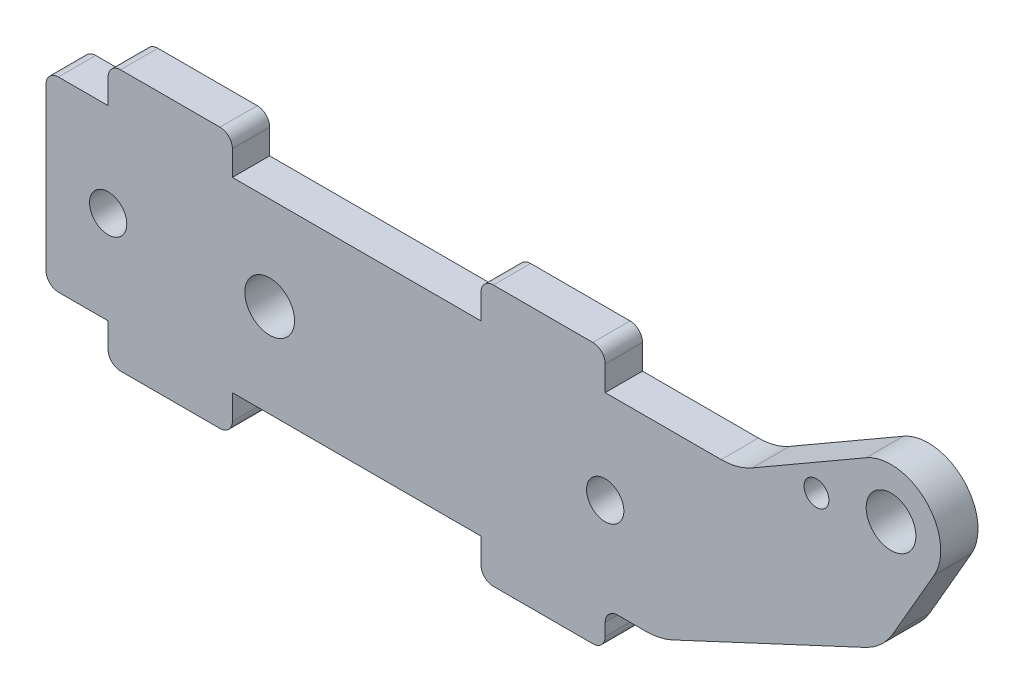
SolidWorks part; units mm, degrees
material "Thornel Mat VMA"
ref_plane "前视基准面" through (0, 0, 0) normal (0, 0, 1) x (1, 0, 0)
ref_plane "上视基准面" through (0, 0, 0) normal (0, 1, 0) x (1, 0, 0)
ref_plane "右视基准面" through (0, 0, 0) normal (1, 0, 0) x (0, 0, -1)
sketch "草图1" plane through (0, 0, 0) normal (0, 0, 1) x (1, 0, 0)
  line L0 (0, 0) -> (45, 0) construction
  line L1 (0, 7.5) -> (5, 7.5)
  line L2 (5, 7.5) -> (5, 10.5)
  line L3 (5, 10.5) -> (15, 10.5)
  line L4 (15, 10.5) -> (15, 7.5)
  line L5 (15, 7.5) -> (35, 7.5)
  line L6 (15, -7.5) -> (35, -7.5)
  line L7 (15, -10.5) -> (15, -7.5)
  line L8 (5, -10.5) -> (15, -10.5)
  line L9 (5, -7.5) -> (5, -10.5)
  line L10 (0, -7.5) -> (5, -7.5)
  line L11 (0, 7.5) -> (0, -7.5)
  line L12 (66, 13.4641) -> (56.8301, 8.1699)
  line L13 (35, 7.5) -> (35, 10.5)
  line L14 (35, 10.5) -> (45, 10.5)
  line L15 (45, 10.5) -> (45, 7.5)
  line L16 (45, 7.5) -> (54.3301, 7.5)
  line L17 (45, -10.5) -> (45, -7.5)
  line L18 (35, -10.5) -> (45, -10.5)
  line L19 (35, -7.5) -> (35, -10.5)
  line L20 (45, -7.5) -> (48.2923, -7.5)
  line L21 (68.1349, 2.2336) -> (71.4641, 8)
  line L22 (50.4054, -7.0315) -> (65.9178, 0.202)
  circle A0 centre (68, 10) radius 2
  arc A1 (71.4641, 8) -> (66, 13.4641) centre (68, 10) ccw
  arc A2 (56.8301, 8.1699) -> (54.3301, 7.5) centre (54.3301, 12.5) cw
  arc A3 (50.4054, -7.0315) -> (48.2923, -7.5) centre (48.2923, -2.5) cw
  circle A4 centre (5, 0) radius 1.5
  circle A5 centre (45, 0) radius 1.5
  arc A6 (65.9178, 0.202) -> (68.1349, 2.2336) centre (63.8047, 4.7336) ccw
  circle A7 centre (18, 0) radius 2
  circle A8 centre (62, 9) radius 1
  dimension "D6" = 10
  dimension "D5" = 23
  dimension "D10" = 8
  dimension "D13" = 30
  dimension "D14" = 5
  dimension "D15" = 10
  dimension "D16" = 5
  dimension "D17" = 3
  dimension "D12" = 5
  dimension "D7" = 4
  dimension "D20" = 5
  dimension "D21" = 4
  dimension "D22" = 3
  dimension "D23" = 2
  dimension "D24" = 9
  dimension "D25" = 17
  dimension "D1" = 15
  dimension "D2" = 3
  dimension "D3" = 5
  dimension "D4" = 10
  dimension "D8" = 20
  dimension "D9" = 10
  dimension "D11" = 60
  dimension "D18" = 8
  dimension "D19" = 25
extrude "凸台-拉伸1" add sketch "草图1" along normal blind 3
fillet "圆角1" radius 1 10 edges at (45, -10.5, 1.5) (35, -10.5, 1.5) (15, -10.5, 1.5) (0, -7.5, 1.5) (5, -10.5, 1.5) (5, 10.5, 1.5) (15, 10.5, 1.5) (35, 10.5, 1.5) (45, 10.5, 1.5) (0, 7.5, 1.5)
fillet "圆角2" radius 1 1 edges at (45, -7.5, 1.5)
